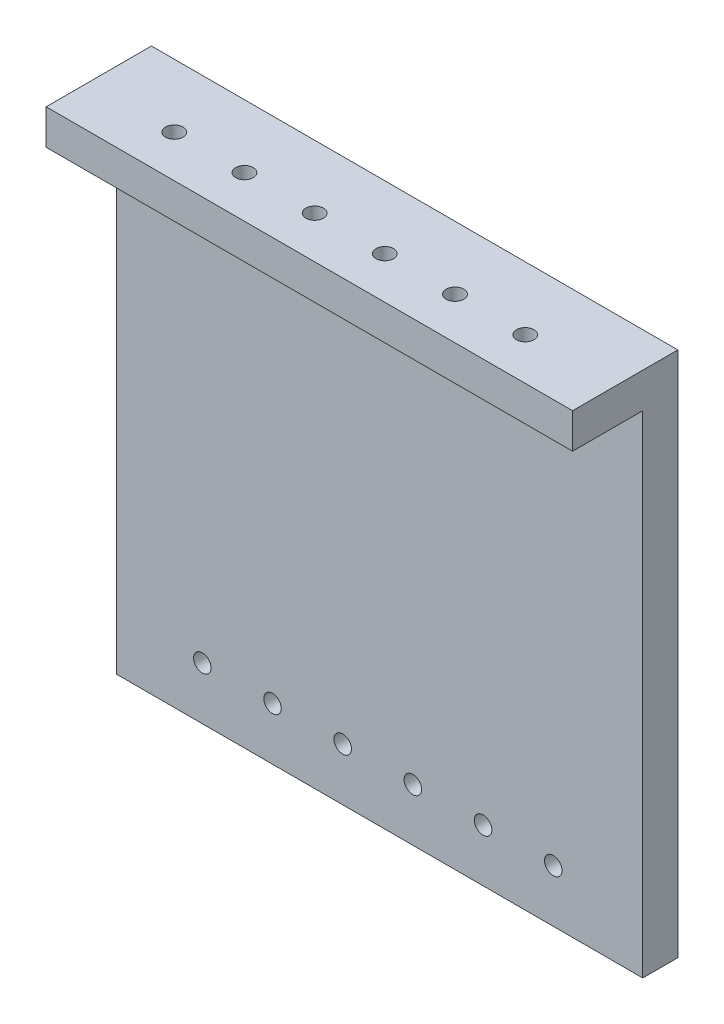
SolidWorks part; units mm, degrees
ref_plane "Front Plane" through (0, 0, 0) normal (0, 0, 1) x (1, 0, 0)
ref_plane "Top Plane" through (0, 0, 0) normal (0, 1, 0) x (1, 0, 0)
ref_plane "Right Plane" through (0, 0, 0) normal (1, 0, 0) x (0, 0, -1)
sketch "Sketch1" plane through (0, 0, 0) normal (0, 0, 1) x (1, 0, 0)
  line L1 (-37.5, -37.5) -> (37.5, -37.5)
  line L2 (-37.5, -37.5) -> (-37.5, 37.5)
  line L3 (-37.5, 37.5) -> (37.5, 37.5)
  line L4 (37.5, -37.5) -> (37.5, 37.5)
  line L5 (-37.5, -37.5) -> (37.5, 37.5) construction
  line L6 (-37.5, 37.5) -> (37.5, -37.5) construction
  circle A0 centre (-25.25, -30) radius 1.25
  circle A1 centre (-15.25, -30) radius 1.25
  circle A2 centre (-5.25, -30) radius 1.25
  circle A3 centre (4.75, -30) radius 1.25
  circle A4 centre (14.75, -30) radius 1.25
  circle A5 centre (24.75, -30) radius 1.25
  point P0 (0, 0)
  dimension "D3" = 7.5
  dimension "D1" = 75
  dimension "D2" = 75
  dimension "D4" = 12.25
  dimension "D5" = 6
extrude "Boss-Extrude1" add sketch "Sketch1" along normal blind 5
sketch "Sketch2" plane through (0, 0, 5) normal (0, 0, 1) x (1, 0, 0)
  line L0 (37.5, -37.5) -> (37.5, 37.5) construction
  line L1 (-37.5, 37.5) -> (37.5, 37.5)
  line L2 (-37.5, 37.5) -> (-37.5, 32.5)
  line L3 (-37.5, 32.5) -> (37.5, 32.5)
  line L4 (37.5, 37.5) -> (37.5, 32.5)
  dimension "D1" = 5
extrude "Boss-Extrude2" add sketch "Sketch2" along normal blind 10
sketch "Sketch3" plane through (0, 37.5, 0) normal (0, 1, 0) x (1, 0, 0)
  line L0 (-37.5, -15) -> (-37.5, 0) construction
  line L1 (37.5, -15) -> (-37.5, -15) construction
  circle A0 centre (-25.25, -9) radius 1.25
  circle A1 centre (-15.25, -9) radius 1.25
  circle A2 centre (-5.25, -9) radius 1.25
  circle A3 centre (4.75, -9) radius 1.25
  circle A4 centre (14.75, -9) radius 1.25
  circle A5 centre (24.75, -9) radius 1.25
  dimension "D1" = 6
  dimension "D2" = 12.25
  dimension "D3" = 6
extrude "Cut-Extrude1" cut sketch "Sketch3" against normal up to next
